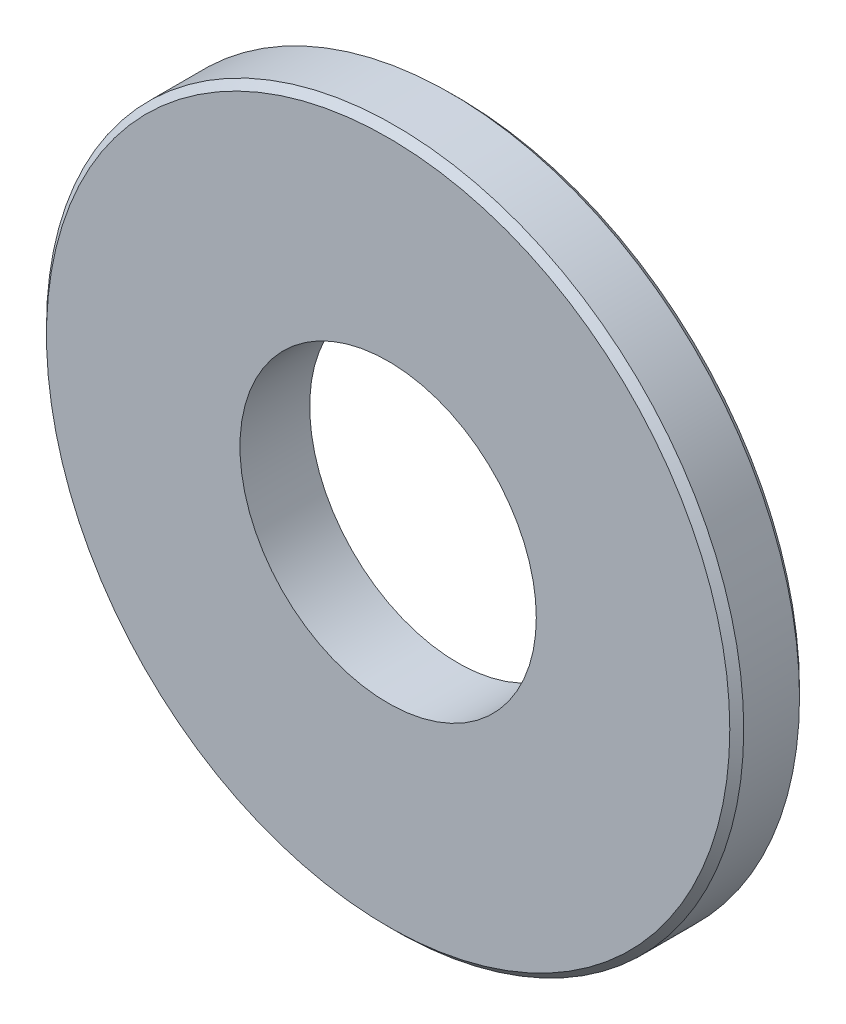
SolidWorks part; units mm, degrees
material "Alloy Steel"
ref_plane "Front Plane" through (0, 0, 0) normal (0, 0, 1) x (1, 0, 0)
ref_plane "Top Plane" through (0, 0, 0) normal (0, 1, 0) x (1, 0, 0)
ref_plane "Right Plane" through (0, 0, 0) normal (1, 0, 0) x (0, 0, -1)
sketch "Sketch1" plane through (0, 0, 0) normal (0, 0, 1) x (1, 0, 0)
  circle A0 centre (0, 0) radius 10
  circle A1 centre (0, 0) radius 4.25
  dimension "D1" = 20
  dimension "D2" = 8.5
extrude "Boss-Extrude1" add sketch "Sketch1" along normal blind 2
chamfer "Chamfer1" distance 0.2 angle 45 2 edges at (10, 0, 0) (10, 0, 2)
